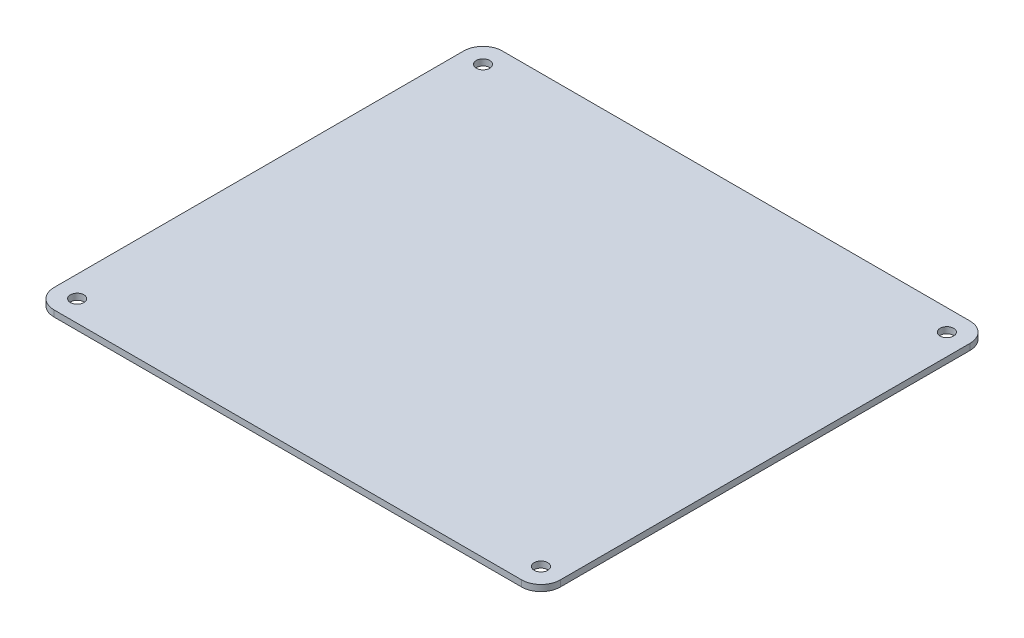
SolidWorks part; units mm, degrees
ref_plane "Plan de face" through (0, 0, 0) normal (0, 0, 1) x (1, 0, 0)
ref_plane "Plan de dessus" through (0, 0, 0) normal (0, 1, 0) x (1, 0, 0)
ref_plane "Plan de droite" through (0, 0, 0) normal (1, 0, 0) x (0, 0, -1)
sketch "Esquisse1" plane through (0, 0, 0) normal (0, 1, 0) x (1, 0, 0)
  line L0 (-65.5, 52.5) -> (-60, 52.5) construction
  line L1 (-60.5, 58) -> (60.5, 58)
  line L2 (-65.5, 53) -> (-65.5, -53)
  line L3 (-60.5, -58) -> (60.5, -58)
  line L4 (65.5, 53) -> (65.5, -53)
  line L5 (-65.5, 58) -> (65.5, -58) construction
  line L6 (-65.5, -58) -> (65.5, 58) construction
  line L7 (-60, 58) -> (-60, 52.5) construction
  line L8 (0, 0) -> (0, 58) construction
  line L9 (0, 0) -> (65.5, 0) construction
  circle A0 centre (-60, 52.5) radius 1.75
  circle A1 centre (60, 52.5) radius 1.75
  circle A2 centre (60, -52.5) radius 1.75
  circle A3 centre (-60, -52.5) radius 1.75
  arc A4 (-65.5, -53) -> (-60.5, -58) centre (-60.5, -53) ccw
  arc A5 (60.5, -58) -> (65.5, -53) centre (60.5, -53) ccw
  arc A6 (60.5, 58) -> (65.5, 53) centre (60.5, 53) cw
  arc A7 (-60.5, 58) -> (-65.5, 53) centre (-60.5, 53) ccw
  point P0 (0, 0)
  dimension "D5" = 3.5
  dimension "D6" = 5
  dimension "D3" = 105
  dimension "D4" = 60
  dimension "D1" = 116
  dimension "D2" = 131
extrude "Boss.-Extru.1" add sketch "Esquisse1" along normal mid plane 1.61
